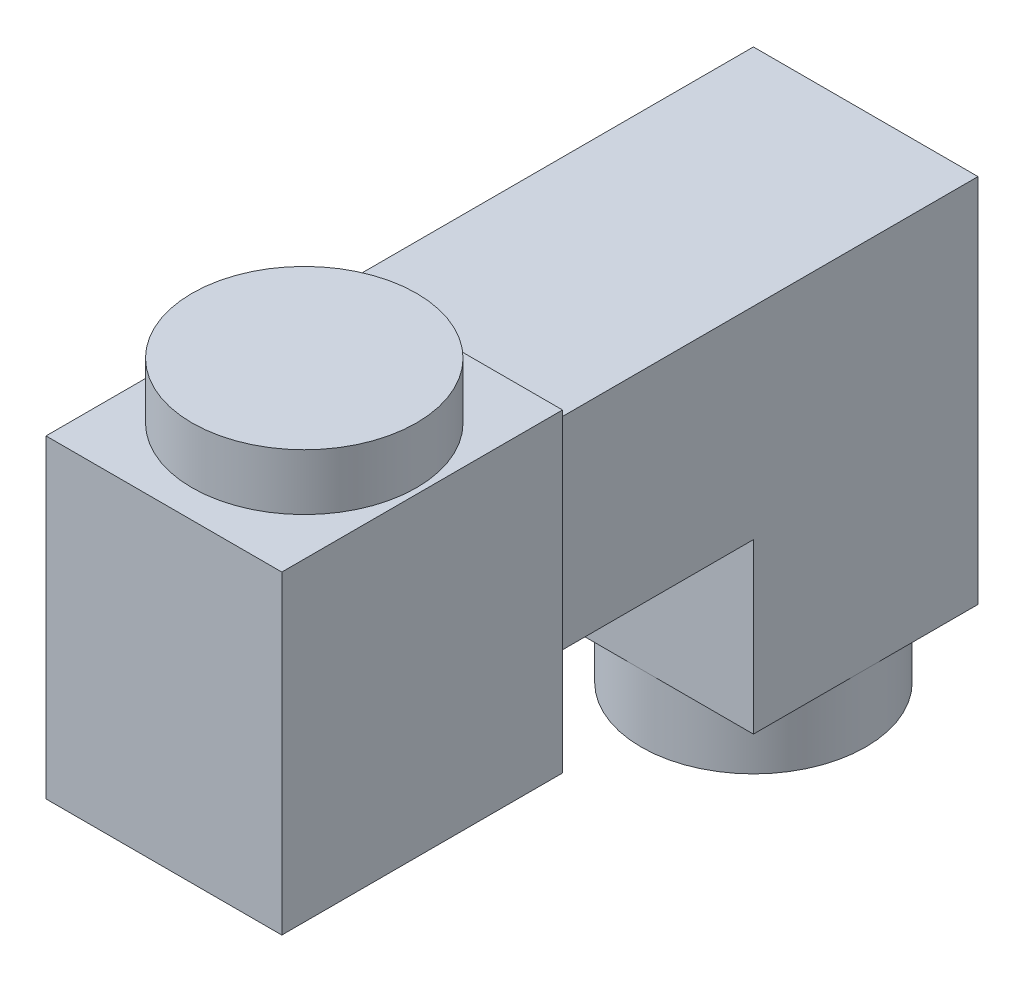
SolidWorks part; units mm, degrees
ref_plane "Plan de face" through (0, 0, 0) normal (0, 0, 1) x (1, 0, 0)
ref_plane "Plan de dessus" through (0, 0, 0) normal (0, 1, 0) x (1, 0, 0)
ref_plane "Plan de droite" through (0, 0, 0) normal (1, 0, 0) x (0, 0, -1)
sketch "Esquisse1" plane through (0, 0, 0) normal (1, 0, 0) x (0, 0, -1)
  line L0 (141.1854, 205.2856) -> (204.6854, 205.2856) construction
  line L6 (144.3932, 155.3) -> (169.3932, 155.3)
  line L7 (144.3932, 155.3) -> (144.3932, 183.3)
  line L8 (144.3932, 183.3) -> (169.3932, 183.3)
  line L9 (169.3932, 155.3) -> (169.3932, 183.3)
  dimension "D1" = 63.5
  dimension "D2" = 28
  dimension "D3" = 25
extrude "Boss.-Extru.1" add sketch "Esquisse1" along normal blind 21
sketch "Esquisse2" plane through (0, 0, -169.3932) normal (0, 0, -1) x (-1, 0, 0)
  line L0 (-10.5, 183.3) -> (-10.5, 155.3) construction
  line L1 (-21, 183.3) -> (0, 183.3) construction
  line L2 (-21, 155.3) -> (0, 155.3) construction
  line L3 (-20.5, 182.3) -> (-0.5, 182.3)
  line L4 (-20.5, 182.3) -> (-20.5, 164.3)
  line L5 (-0.5, 182.3) -> (-0.5, 164.3)
  line L6 (-20.5, 164.3) -> (-0.5, 164.3)
  line L7 (-20.5, 182.3) -> (-0.5, 164.3) construction
  line L8 (-0.5, 182.3) -> (-20.5, 164.3) construction
  point P7 (-10.5, 173.3)
  dimension "D1" = 20
  dimension "D2" = 18
  dimension "D3" = 10
extrude "Boss.-Extru.2" add sketch "Esquisse2" along normal blind 37.5
sketch "Esquisse3" plane through (0, 164.3, 0) normal (0, -1, 0) x (1, 0, 0)
  line L0 (0.5, -206.8932) -> (0.5, -169.3932) construction
  line L1 (0.5, -186.8932) -> (20.5, -186.8932)
  line L2 (0.5, -186.8932) -> (0.5, -206.8932)
  line L3 (0.5, -206.8932) -> (20.5, -206.8932)
  line L4 (20.5, -186.8932) -> (20.5, -206.8932)
  dimension "D1" = 20
extrude "Boss.-Extru.3" add sketch "Esquisse3" along normal blind 15
sketch "Esquisse5" plane through (0, 183.3, 0) normal (0, 1, 0) x (1, 0, 0)
  line L0 (21, 156.8932) -> (0, 156.8932) construction
  line L1 (21, 169.3932) -> (21, 144.3932) construction
  line L2 (0, 144.3932) -> (0, 169.3932) construction
  line L3 (10.5, 169.3932) -> (10.5, 144.3932) construction
  line L4 (21, 169.3932) -> (0, 169.3932) construction
  line L5 (21, 144.3932) -> (0, 144.3932) construction
  circle A0 centre (10.5, 156.8932) radius 10
  dimension "D1" = 20
extrude "Boss.-Extru.4" add sketch "Esquisse5" along normal blind 5
sketch "Esquisse6" plane through (0, 149.3, 0) normal (0, -1, 0) x (-1, 0, 0)
  line L0 (-0.5, 196.8932) -> (-20.5, 196.8932) construction
  line L1 (-0.5, 186.8932) -> (-0.5, 206.8932) construction
  line L2 (-20.5, 206.8932) -> (-20.5, 186.8932) construction
  circle A0 centre (-10.5, 196.8932) radius 10
  dimension "D1" = 20
extrude "Boss.-Extru.5" add sketch "Esquisse6" along normal blind 6
